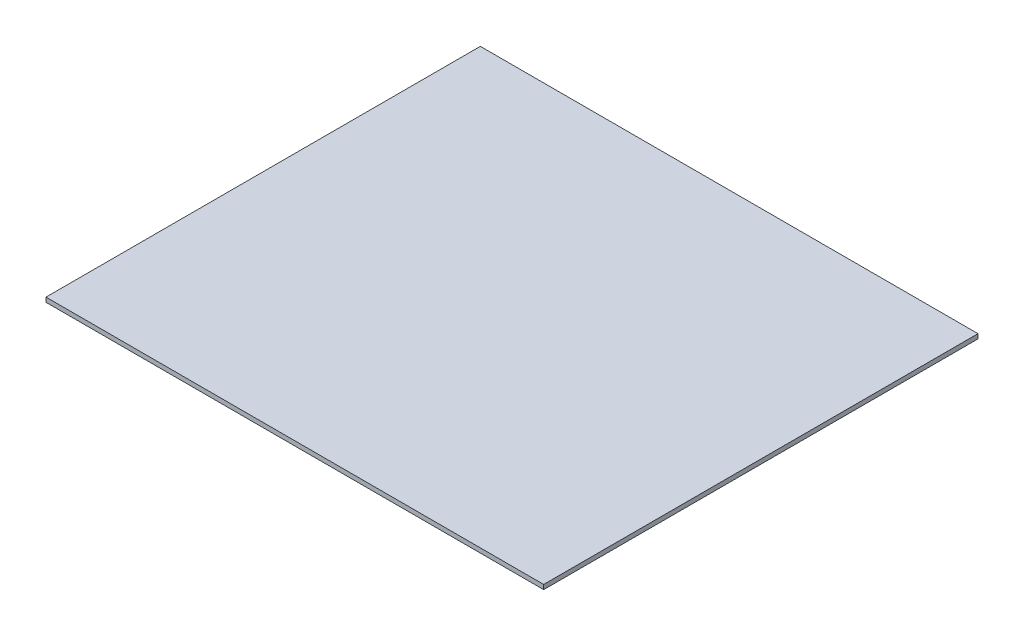
SolidWorks part; units mm, degrees
ref_plane "Front Plane" through (0, 0, 0) normal (0, 0, 1) x (1, 0, 0)
ref_plane "Top Plane" through (0, 0, 0) normal (0, 1, 0) x (1, 0, 0)
ref_plane "Right Plane" through (0, 0, 0) normal (1, 0, 0) x (0, 0, -1)
sketch "Sketch1" plane through (0, 0, 0) normal (0, 1, 0) x (1, 0, 0)
  line L1 (698.5, 609.6) -> (-698.5, 609.6)
  line L2 (698.5, 609.6) -> (698.5, -609.6)
  line L3 (698.5, -609.6) -> (-698.5, -609.6)
  line L4 (-698.5, 609.6) -> (-698.5, -609.6)
  line L5 (698.5, 609.6) -> (-698.5, -609.6) construction
  line L6 (698.5, -609.6) -> (-698.5, 609.6) construction
  point P0 (0, 0)
  dimension "D1" = 1219.2
  dimension "D2" = 1397
extrude "Boss-Extrude1" add sketch "Sketch1" along normal blind 12.7 contours L1 L4 L3 L2
